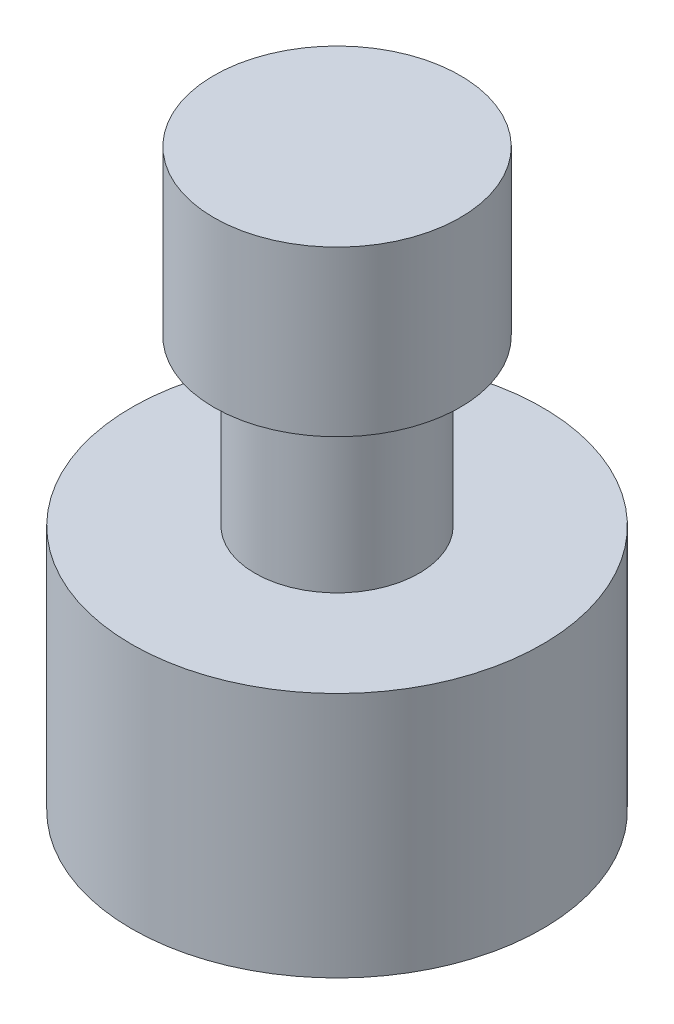
SolidWorks part; units mm, degrees
ref_plane "Front Plane" through (0, 0, 0) normal (0, 0, 1) x (1, 0, 0)
ref_plane "Top Plane" through (0, 0, 0) normal (0, 1, 0) x (1, 0, 0)
ref_plane "Right Plane" through (0, 0, 0) normal (1, 0, 0) x (0, 0, -1)
sketch "Sketch1" plane through (0, 0, 0) normal (0, 0, 1) x (1, 0, 0)
  line L0 (35, 30) -> (50, 30)
  line L1 (0, 0) -> (50, 0)
  line L2 (0, 0) -> (0, 30)
  line L3 (0, 30) -> (15, 30)
  line L4 (50, 0) -> (50, 30)
  line L6 (15, 30) -> (15, 50)
  line L8 (35, 30) -> (35, 50)
  line L9 (25, 70) -> (25, 0) construction
  line L11 (10, 50) -> (15, 50)
  line L12 (10, 50) -> (10, 70)
  line L13 (10, 70) -> (40, 70)
  line L14 (40, 50) -> (40, 70)
  line L17 (35, 50) -> (40, 50)
  point P5 (50.7428, 29.6821)
  point P10 (50.7428, 49.3756)
  dimension "D1" = 20
  dimension "D2" = 20
  dimension "D3" = 30
  dimension "D4" = 50
  dimension "D5" = 20
  dimension "D6" = 30
revolve "Revolve2" add sketch "Sketch1" angle 360 about L9
